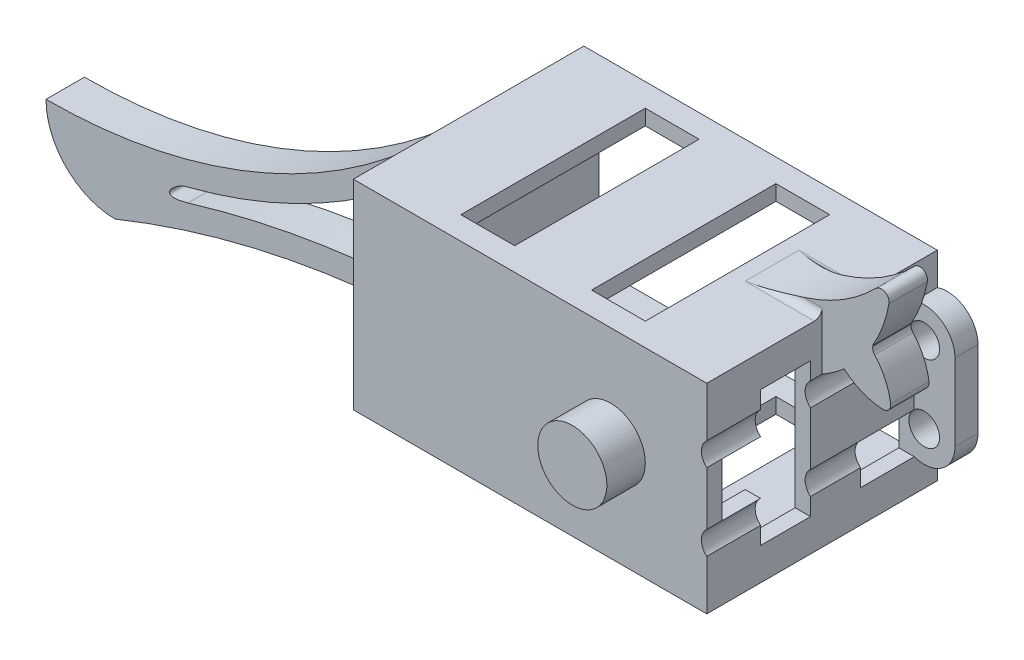
SolidWorks part; units mm, degrees
other "Markup1"
sketch "Sketch15" plane through (31.9332, 19.9963, 30) normal (0.1157, 0.1665, 0.9792) x (0.2474, -0.9596, 0.1339)
other "Markup2"
sketch "Sketch16" plane through (-78, 19.9963, 30) normal (-0.6723, 0.4833, 0.5608) x (0.1241, -0.6733, 0.7289)
material "Custom Plastic"
ref_plane "Front Plane" through (0, 0, 0) normal (0, 0, 1) x (1, 0, 0)
ref_plane "Top Plane" through (0, 0, 0) normal (0, 1, 0) x (1, 0, 0)
ref_plane "Right Plane" through (0, 0, 0) normal (1, 0, 0) x (0, 0, -1)
sketch "Sketch1" plane through (0, 0, 0) normal (0, 0, 1) x (1, 0, 0)
  line L0 (-23, 13) -> (-23, -13)
  line L1 (-20, 10) -> (20, 10) construction
  line L2 (-20, 10) -> (-20, -10) construction
  line L3 (-20, -10) -> (20, -10) construction
  line L4 (20, 10) -> (20, -10) construction
  line L5 (-20, 10) -> (20, -10) construction
  line L6 (-20, -10) -> (20, 10) construction
  line L7 (-23, -13) -> (23, -13)
  line L8 (23, 13) -> (23, -13)
  line L9 (-23, 13) -> (23, 13)
  point P0 (0, 0)
  dimension "D1" = 40
  dimension "D2" = 20
  dimension "D3" = 3
extrude "Boss-Extrude3" add sketch "Sketch1" along normal blind 30
shell "Shell1" thickness 2
sketch "Sketch2" plane through (0, 0, 30) normal (0, 0, 1) x (1, 0, 0)
  line L0 (0, 5) -> (0, -5) construction
  line L1 (-21, 11) -> (21, 11) construction
  line L2 (-21, 11) -> (-21, -11) construction
  line L3 (-21, -11) -> (21, -11) construction
  line L4 (21, 11) -> (21, -11) construction
  line L5 (-24.3, 5) -> (24.3, 5) construction
  line L6 (-24.3, 5) -> (-24.3, -5) construction
  line L7 (-24.3, -5) -> (24.3, -5) construction
  line L8 (24.3, 5) -> (24.3, -5) construction
  line L9 (-24.3, 5) -> (24.3, -5) construction
  line L10 (-24.3, -5) -> (24.3, 5) construction
  line L11 (-24.3, 0) -> (24.3, 0) construction
  line L13 (-28.3, 9) -> (28.3, 9)
  line L14 (-28.3, 9) -> (-28.3, -9)
  line L15 (-28.3, -9) -> (28.3, -9)
  line L16 (28.3, 9) -> (28.3, -9)
  line L17 (-28.3, 9) -> (28.3, -9) construction
  line L18 (-28.3, -9) -> (28.3, 9) construction
  circle A0 centre (-24.3, 5) radius 2
  circle A1 centre (24.3, 5) radius 2
  circle A2 centre (24.3, -5) radius 2
  circle A3 centre (-24.3, -5) radius 2
  circle A4 centre (-24.3, 5) radius 4
  circle A5 centre (-24.3, -5) radius 4
  circle A6 centre (24.3, 5) radius 4
  circle A7 centre (24.3, -5) radius 4
  point P6 (0, 0)
  point P28 (0, 0)
  line M7 (-23, 13) -> (-23, -13)
  line M9 (23, -13) -> (23, 13)
  dimension "D3" = 4
  dimension "D1" = 10
  dimension "D2" = 48.6
  dimension "D4" = 2
  dimension "D5" = 2
  dimension "D6" = 2
  dimension "D7" = 2
sketch "Sketch4" plane through (0, 0, 0) normal (0, 0, 1) x (1, 0, 0)
  line L0 (0, 5) -> (0, -5) construction
  line L1 (-20, 10) -> (20, 10) construction
  line L2 (-20, 10) -> (-20, -10) construction
  line L3 (-20, -10) -> (20, -10) construction
  line L4 (20, 10) -> (20, -10) construction
  line L5 (-24.3, 5) -> (24.3, 5) construction
  line L6 (-24.3, 5) -> (-24.3, -5) construction
  line L7 (-24.3, -5) -> (24.3, -5) construction
  line L8 (24.3, 5) -> (24.3, -5) construction
  line L9 (-24.3, 5) -> (24.3, -5) construction
  line L10 (-24.3, -5) -> (24.3, 5) construction
  line L11 (-24.3, 0) -> (24.3, 0) construction
  line L13 (-28.3, 9) -> (28.3, 9)
  line L14 (-28.3, 9) -> (-28.3, -9)
  line L15 (-28.3, -9) -> (28.3, -9)
  line L16 (28.3, 9) -> (28.3, -9)
  line L17 (-28.3, 9) -> (28.3, -9) construction
  line L18 (-28.3, -9) -> (28.3, 9) construction
  circle A0 centre (-24.3, 5) radius 2
  circle A1 centre (24.3, 5) radius 2
  circle A2 centre (24.3, -5) radius 2
  circle A3 centre (-24.3, -5) radius 2
  circle A4 centre (-24.3, 5) radius 4
  circle A5 centre (-24.3, -5) radius 4
  circle A6 centre (24.3, 5) radius 4
  circle A7 centre (24.3, -5) radius 4
  point P6 (0, 0)
  point P28 (0, 0)
  dimension "D3" = 4
  dimension "D1" = 10
  dimension "D2" = 48.6
  dimension "D4" = 2
  dimension "D5" = 2
  dimension "D6" = 2
  dimension "D7" = 2
extrude "Cut-Extrude2" cut sketch "Sketch4" along normal through all contours A1 | A2 | A0 | A3
extrude "Boss-Extrude4" add sketch "Sketch2" against normal blind 3 contours A6 A1 M9 | A7 L16 A6 M9 | A7 A2 M9 | A4 A0 M7 | L14 A5 A4 M7 | A5 A3 M7
sketch "Sketch5" plane through (23, 0, 0) normal (1, 0, 0) x (0, 0, -1)
  line L0 (-27, 8.7829) -> (0, 8.7829)
  line L1 (0, 6.5199) -> (0, 13) construction
  line L2 (-27, 8.7829) -> (-27, -8.7829)
  line L3 (-27, -8.7829) -> (0, -8.7829)
  line L4 (0, -13) -> (0, -6.5199) construction
  line L5 (0, -8.7829) -> (0, 8.7829)
  line L6 (-20, 8.7829) -> (-20, -8.7829)
  line L7 (-13.5, 8.7829) -> (-13.5, -8.7829) construction
  line L8 (-7, 8.7829) -> (-7, -8.7829)
  line L9 (-7, 3.4801) -> (0, 3.4801)
  line L10 (0, 3.4801) -> (-27, 3.4801) construction
  line L11 (0, 3.4801) -> (0, -3.4801)
  line L12 (0, -3.4801) -> (-7, -3.4801)
  line L13 (0, -3.4801) -> (-27, -3.4801) construction
  line L14 (-2, 3.4801) -> (-2, -3.4801)
  line L15 (-20, 3.4801) -> (-27, 3.4801)
  line L16 (-20, -3.4801) -> (-27, -3.4801)
  line M8 (-27, 8.7829) -> (-27, 6.5199)
  line M9 (-27, 6.5199) -> (0, 6.5199)
  dimension "D1" = 7
  dimension "D2" = 2
extrude "Cut-Extrude4" cut sketch "Sketch5" against normal through all contours L6 L0 M8 M9 | L15 L6 L2 M9 | L6 L16 L2 L3 | L0 L7 L8 M9 | L7 L3 L8 M9 | L14 L9 L8 L12
sketch "Sketch6" plane through (0, 13, 0) normal (0, 1, 0) x (1, 0, 0)
  line L0 (-23, -30) -> (-23, 0)
  line L1 (-23, 0) -> (23, 0)
  line L2 (23, 0) -> (23, -30)
  line L3 (23, -30) -> (23, 0) construction
  line L4 (23, -30) -> (-23, -30) construction
  line L5 (23, -30) -> (-23, -30)
  line L6 (20, -27) -> (-20, -27)
  line L7 (-20, -27) -> (-20, -3)
  line L8 (-20, -3) -> (20, -3)
  line L9 (20, -3) -> (20, -27)
  line L10 (12, -27) -> (12, -3)
  line L11 (5, -27) -> (5, -3)
  line L12 (0, -27) -> (0, -3) construction
  line L13 (-12, -27) -> (-12, -3)
  line L14 (-5, -27) -> (-5, -3)
  dimension "D2" = 7
  dimension "D3" = 5
  dimension "D1" = 3
extrude "Cut-Extrude6" cut sketch "Sketch6" against normal through all contours L11 L6 L10 L8 | L6 L14 L8 L13
sketch "Sketch7" plane through (-23, 0, 0) normal (-1, 0, 0) x (0, 0, 1)
  line L0 (30, -13) -> (0, -13) construction
  line L7 (0, -13) -> (27, -13)
  line L18 (20, -8.7829) -> (0, -8.7829)
  line L19 (20, -8.7829) -> (20, 6.5199)
  line L20 (20, 6.5199) -> (0, 6.5199)
  line L21 (0, -8.7829) -> (0, 6.5199)
  line L22 (27, -8.7829) -> (7, -8.7829)
  line L23 (27, -8.7829) -> (27, 8.7829)
  line L24 (27, 8.7829) -> (7, 8.7829)
  line L25 (7, -8.7829) -> (7, 8.7829)
  line M5 (7, 6.5199) -> (7, 8.7829)
  line M6 (7, 8.7829) -> (13.5, 8.7829)
  line M7 (13.5, 8.7829) -> (13.5, 6.5199)
  line M8 (13.5, 6.5199) -> (20, 6.5199)
  line M9 (20, 6.5199) -> (20, 8.7829)
  line M15 (0, 6.5199) -> (7, 6.5199)
extrude "Boss-Extrude13" add sketch "Sketch7" against normal up to surface (2 mm away) contours L24 M9 M7 M8 | L20 M7 M6 M5 | L25 L18 L19 L20 M8 | L18 L25 L21 M15 up to face at (-21, 6.1315, 23.5)
sketch "Sketch9" plane through (0, 0, 0) normal (0, 0, 1) x (1, 0, 0)
  line L0 (0, 5) -> (0, -5) construction
  line L1 (-20, 10) -> (20, 10) construction
  line L2 (-20, 10) -> (-20, -10) construction
  line L3 (-20, -10) -> (20, -10) construction
  line L4 (20, 10) -> (20, -10) construction
  line L5 (-24.3, 5) -> (24.3, 5) construction
  line L6 (-24.3, 5) -> (-24.3, -5) construction
  line L7 (-24.3, -5) -> (24.3, -5) construction
  line L8 (24.3, 5) -> (24.3, -5) construction
  line L9 (-24.3, 5) -> (24.3, -5) construction
  line L10 (-24.3, -5) -> (24.3, 5) construction
  line L11 (-24.3, 0) -> (24.3, 0) construction
  line L12 (-24.3, 5) -> (-24.3, -5)
  line L13 (-28.3, 9) -> (28.3, 9)
  line L14 (-28.3, 9) -> (-28.3, -9)
  line L15 (-28.3, -9) -> (28.3, -9)
  line L16 (28.3, 9) -> (28.3, -9)
  line L17 (-28.3, 9) -> (28.3, -9) construction
  line L18 (-28.3, -9) -> (28.3, 9) construction
  line L19 (-24.3, 5) -> (10.5, 5)
  line L20 (-24.3, -5) -> (10.5, -5)
  line L21 (10.5, 5) -> (10.5, -5)
  circle A0 centre (-24.3, 5) radius 2
  circle A1 centre (24.3, 5) radius 2
  circle A2 centre (24.3, -5) radius 2
  circle A3 centre (-24.3, -5) radius 2
  circle A4 centre (-24.3, 5) radius 4
  circle A5 centre (-24.3, -5) radius 4
  circle A6 centre (24.3, 5) radius 4
  circle A7 centre (24.3, -5) radius 4
  circle A8 centre (10.5, 0) radius 4.5
  point P6 (0, 0)
  point P28 (0, 0)
  dimension "D3" = 4
  dimension "D9" = 9
  dimension "D1" = 10
  dimension "D2" = 48.6
  dimension "D8" = 34.8
  dimension "D4" = 2
  dimension "D5" = 2
  dimension "D6" = 2
  dimension "D7" = 2
extrude "Boss-Extrude16" add sketch "Sketch9" against normal blind 5 contours L21 A8 | L21 A8
sketch "Sketch14" plane through (0, 0, 0) normal (0, 0, -1) x (-1, 0, 0)
  line L0 (69, 39) -> (69, -13)
  line L1 (-23, 13) -> (69, 13)
  line L2 (-23, 39) -> (-23, -13)
  line L3 (-23, -13) -> (69, -13) construction
  line L4 (23, 39) -> (23, -13)
  line L5 (-115, 39) -> (69, 39)
  line L6 (-69, 39) -> (-69, -65)
  line L7 (-23, 13) -> (-115, 13) construction
  line L8 (-115, 39) -> (-115, -65)
  line L9 (-23, -13) -> (-115, -13)
  line L10 (-23, -39) -> (-115, -39)
  line L11 (-23, -39) -> (161, -39)
  line L12 (23, -65) -> (23, -13)
  line L13 (-115, -65) -> (69, -65)
  line L14 (69, -65) -> (69, -13)
  line L15 (-23, -65) -> (-23, -13)
  line L16 (161, 13) -> (69, 13)
  line L17 (161, -13) -> (69, -13) construction
  line L18 (115, 39) -> (115, -13)
  line L19 (115, -65) -> (115, -13)
  line L20 (-14, 13) -> (-14, 22)
  line L21 (69, -13) -> (78, -13) construction
  line L22 (69, -13) -> (69, -22)
  line L23 (69, -22) -> (78, -22)
  line L24 (78, -13) -> (78, -22)
  line L25 (-14, 13) -> (-32, 13) construction
  line L26 (-23, 13) -> (-23, 22)
  line L27 (-14, 22) -> (-32, 22)
  line L28 (-32, 13) -> (-32, 22)
  line L30 (-23, 6.5199) -> (-32, 6.5199)
  line L31 (-23, 6.5199) -> (-23, 13)
  line L32 (-23, 13) -> (-32, 13)
  line L33 (-32, 6.5199) -> (-32, 13)
  line L34 (-23, 6.5199) -> (-21, 6.5199)
  line L35 (-23, 6.5199) -> (-23, 13)
  line L36 (-23, 13) -> (-21, 13)
  line L37 (-21, 6.5199) -> (-21, 13)
  arc A0 (23, -13) -> (69, -22) centre (23, -135.0556) cw
  arc A1 (69, -22) -> (78, -13) centre (69, -13) ccw
  arc A2 (78, -13) -> (23, 13) centre (78, 58.1731) cw
  arc A3 (-14, 13) -> (-30.0176, 19.6985) centre (-14, 35.5) cw
  arc A4 (-31.7134, 18.8176) -> (-29.7214, 13.2831) centre (-14.187, 22) ccw
  arc A5 (-31.9242, 7.6449) -> (-29.85, 12.125) centre (-23.6186, 6.5199) cw
  arc A6 (-23, 14.8784) -> (-30.8725, 6.5125) centre (-31.3814, 14.8784) cw
  arc A7 (-30.0176, 19.6985) -> (-31.7134, 18.8176) centre (-30.7295, 18.9963) ccw
  arc A8 (-29.85, 12.125) -> (-29.7214, 13.2831) centre (-30.5935, 12.7937) ccw
  arc A9 (-31.9242, 7.6449) -> (-30.8725, 6.5125) centre (-30.9332, 7.5106) ccw
  arc A10 (-29.7214, 13.2831) -> (-23, 6.5199) centre (-14.187, 22) ccw
  arc A11 (78, -16) -> (20.6817, 11.0959) centre (78, 58.1731) cw
  arc A12 (23, -10) -> (70.1306, -19.2212) centre (23, -135.0556) cw
  arc A13 (69, -19) -> (75, -13) centre (69, -13) ccw construction
  spline S0 degree 3 poles (59.5435, -15.4585) (63.9567, -16.6758) (61.1597, -13.9287) (59.5435, -13.667) knots 0 0 0 0 1 1 1 1
  point P9 (23, 13)
  point P18 (-69, -13)
  point P25 (69, -39)
  point P30 (78, -13)
  dimension "D5" = 1
  dimension "D1" = 55
  dimension "D2" = 9
  dimension "D3" = 9
  dimension "D4" = 9
  dimension "D6" = 2
  dimension "D7" = 3
extrude "Boss-Extrude18" add sketch "Sketch14" against normal blind 5 from offset 15 offset against normal yes
fillet "Fillet1" radius 1 1 edges at (-23, 8.4072, 17.5)
fillet "Fillet2" radius 1 1 edges at (-23, -10, 17.5)
fillet "Fillet3" radius 1 1 edges at (18.5, 13, 15)
fillet "Fillet4" radius 1 1 edges at (18.5, 13, 20)
mirror "Mirror1" about plane through (0, 0, 30) normal (0, 0, -1) of bodies 119
ref_plane "Plane1" through (0, 0, 30) normal (0, 0, -1) x (-1, 0, 0)
sketch "Sketch17" plane through (0, 0, 30) normal (0, 0, -1) x (-1, 0, 0)
  circle A0 centre (0, 0) radius 100.848
extrude "Cut-Extrude7" cut sketch "Sketch17" along normal through all
